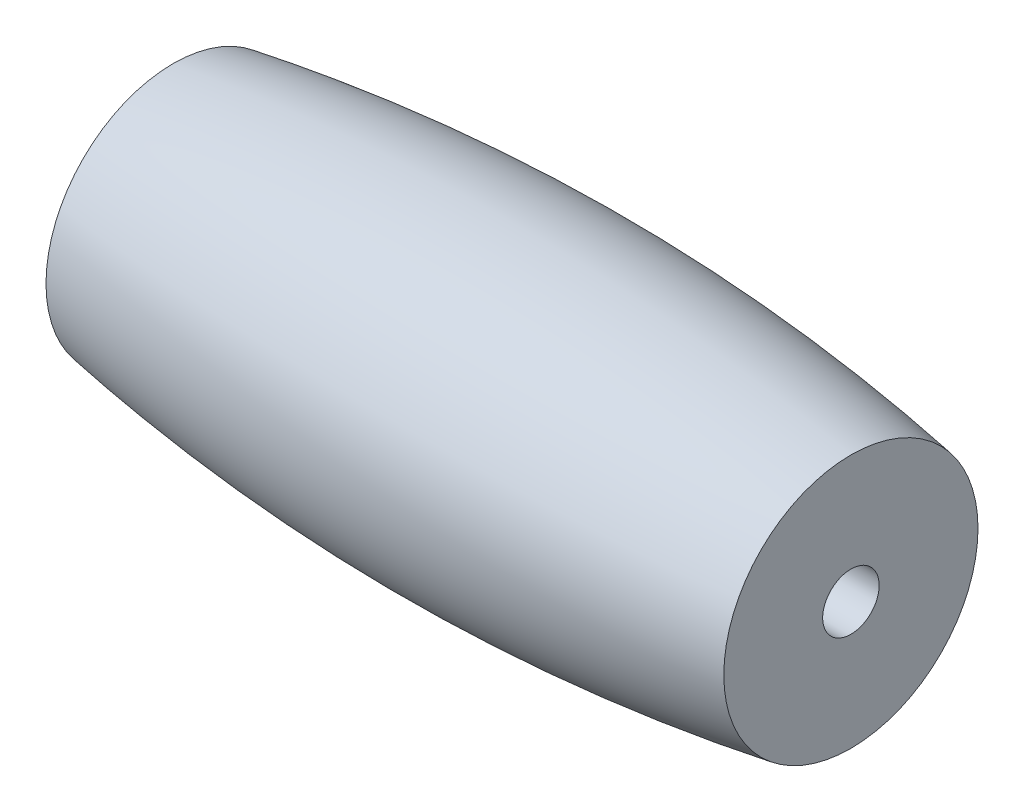
SolidWorks part; units mm, degrees
material "Rubber"
ref_plane "Front Plane" through (0, 0, 0) normal (0, 0, 1) x (1, 0, 0)
ref_plane "Top Plane" through (0, 0, 0) normal (0, 1, 0) x (1, 0, 0)
ref_plane "Right Plane" through (0, 0, 0) normal (1, 0, 0) x (0, 0, -1)
sketch "Sketch1" plane through (0, 0, 0) normal (0, 0, 1) x (1, 0, 0)
  line L0 (11.25, 0) -> (-12.4167, 0) construction
  line L1 (-40.4583, 2) -> (7.5417, 2)
  line L2 (7.5417, 2) -> (7.5417, 9)
  line L3 (-16.4583, 0) -> (-16.4583, 8.125) construction
  line L4 (-40.4583, 2) -> (-40.4583, 9)
  arc A0 (-40.4583, 9) -> (7.5417, 9) centre (-16.4583, -134) cw
  point P7 (-16.4583, 11)
  point P11 (-16.4583, 2)
  point P14 (-16.4583, 11)
  dimension "D1" = 2
  dimension "D2" = 9
  dimension "D3" = 24
  dimension "D4" = 11
revolve "Revolve1" add sketch "Sketch1" angle 360 about L0
